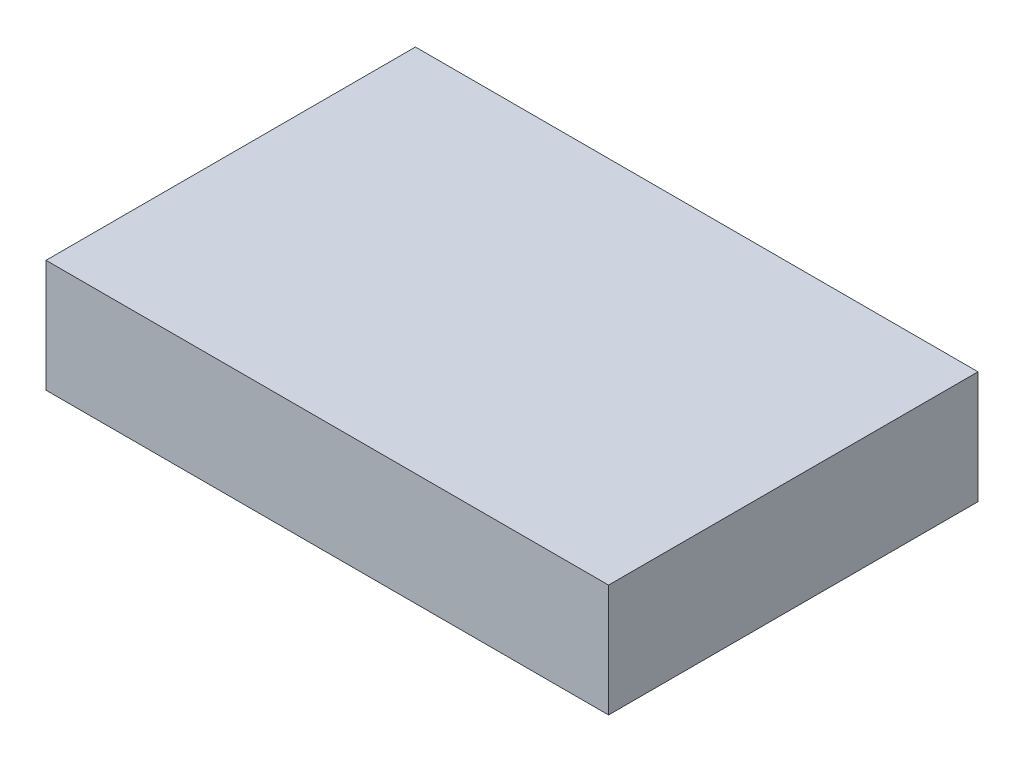
SolidWorks part; units mm, degrees
ref_plane "Front" through (0, 0, 0) normal (0, 0, 1) x (1, 0, 0)
ref_plane "Top" through (0, 0, 0) normal (0, 1, 0) x (1, 0, 0)
ref_plane "Right" through (0, 0, 0) normal (1, 0, 0) x (0, 0, -1)
sketch "Sketch1" plane through (0, 0, 0) normal (0, 1, 0) x (1, 0, 0)
  line L1 (0, 0) -> (85.09, 0)
  line L2 (0, 0) -> (0, 55.88)
  line L3 (0, 55.88) -> (85.09, 55.88)
  line L4 (85.09, 0) -> (85.09, 55.88)
  dimension "D1" = 85.09
  dimension "D2" = 55.88
extrude "Boss-Extrude1" add sketch "Sketch1" along normal blind 17.018
